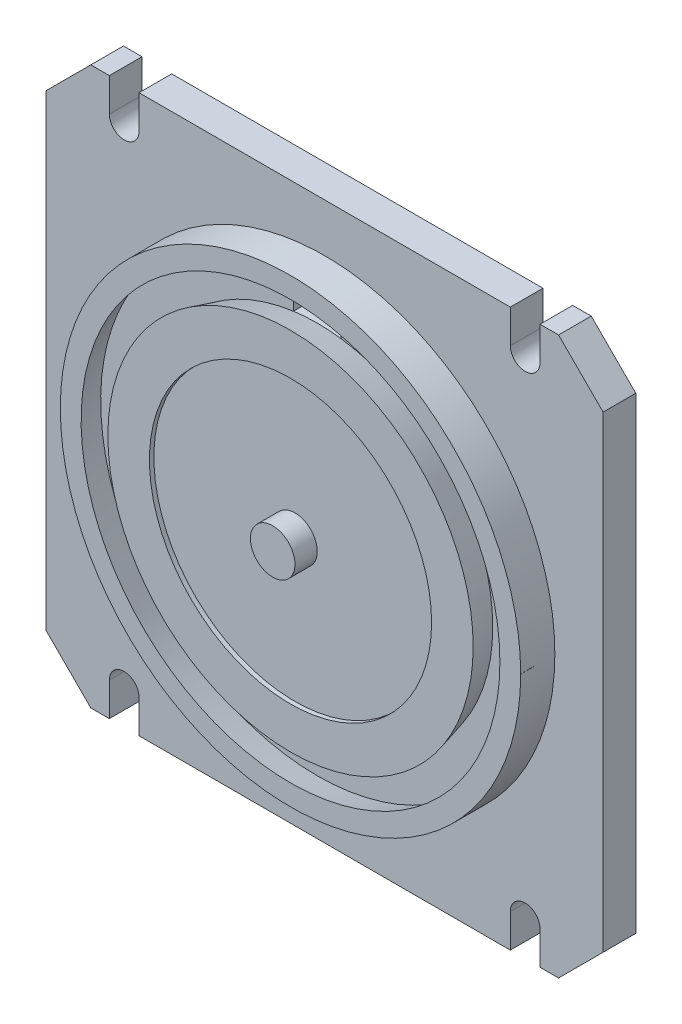
SolidWorks part; units mm, degrees
ref_plane "前视基准面" through (0, 0, 0) normal (0, 0, 1) x (1, 0, 0)
ref_plane "上视基准面" through (0, 0, 0) normal (0, 1, 0) x (1, 0, 0)
ref_plane "右视基准面" through (0, 0, 0) normal (1, 0, 0) x (0, 0, -1)
sketch "草图1" plane through (0, 0, 0) normal (0, 0, 1) x (1, 0, 0)
  line L1 (-187.5, -187.5) -> (187.5, -187.5)
  line L2 (-187.5, -187.5) -> (-187.5, 187.5)
  line L3 (-187.5, 187.5) -> (187.5, 187.5)
  line L4 (187.5, -187.5) -> (187.5, 187.5)
  line L5 (-187.5, -187.5) -> (187.5, 187.5) construction
  line L6 (-187.5, 187.5) -> (187.5, -187.5) construction
  point P0 (0, 0)
  dimension "D1" = 375
extrude "凸台-拉伸1" add sketch "草图1" along normal blind 22
chamfer "倒角1" distance 30 angle 45 4 edges at (187.5, -187.5, 11) (-187.5, -187.5, 11) (-187.5, 187.5, 11) (187.5, 187.5, 11)
sketch "草图2" plane through (0, 0, 22) normal (0, 0, 1) x (1, 0, 0)
  line L0 (135, -187.5) -> (135, -165) construction
  line L1 (-157.5, -187.5) -> (157.5, -187.5) construction
  line L2 (125, -187.5) -> (125, -165)
  line L3 (145, -187.5) -> (145, -165)
  line L4 (0, -12.1) -> (0, 12.1) construction
  line L5 (12.1, 0) -> (-12.1, 0) construction
  arc A0 (125, -187.5) -> (145, -187.5) centre (135, -187.5) ccw
  arc A1 (145, -165) -> (125, -165) centre (135, -165) ccw
  point P4 (135, -176.25)
  dimension "D1" = 20
  dimension "D2" = 135
  dimension "D3" = 165
extrude "切除-拉伸1" cut sketch "草图2" against normal through all
mirror "镜向1" about plane through (0, 0, 0) normal (0, 1, 0) of "切除-拉伸1" second plane through (0, 0, 0) second plane normal (1, 0, 0)
sketch "草图3" plane through (0, 0, 22) normal (0, 0, 1) x (1, 0, 0)
  circle A0 centre (0, 0) radius 155
  dimension "D1" = 310
extrude "凸台-拉伸2" add sketch "草图3" along normal blind 23
sketch "草图4" plane through (0, 0, 45) normal (0, 0, 1) x (1, 0, 0)
  circle A0 centre (0, 0) radius 95
  dimension "D1" = 190
extrude "切除-拉伸2" cut sketch "草图4" against normal blind 3
sketch "草图5" plane through (0, 0, 42) normal (0, 0, 1) x (1, 0, 0)
  circle A0 centre (0, 0) radius 15
  dimension "D1" = 30
extrude "凸台-拉伸3" add sketch "草图5" along normal blind 15
sketch "草图6" plane through (0, 0, 0) normal (1, 0, 0) x (0, 0, -1)
  line L0 (-100.6659, -132) -> (56.0634, -132) construction
  line L1 (31.35, 0) -> (-31.35, 0) construction
  line L2 (0, 0) -> (137.7485, 0) construction
  line L3 (0, -157.5) -> (0, 157.5) construction
  line L4 (-78.5885, -132) -> (-27, -118.1769)
  line L5 (-27, -118.1769) -> (-27, -145.8231)
  line L6 (-27, -145.8231) -> (-78.5885, -132)
  line L7 (-45, 155) -> (-45, -155) construction
  point P13 (-45, -141)
  point P14 (-45, -123)
  dimension "D1" = 132
  dimension "D2" = 30
  dimension "D3" = 18
  dimension "D4" = 18
revolve "切除-旋转1" cut sketch "草图6" angle 360 about L2
sketch "草图7" plane through (0, 0, 27) normal (0, 0, 1) x (1, 0, 0)
  line L0 (-16, 117.0888) -> (-16, 144.9427)
  line L1 (0, 108.8139) -> (0, 216.5114) construction
  line L2 (0, -131.1279) -> (0, 131.1279) construction
  line L3 (16, 117.0888) -> (16, 144.9427)
  circle A0 centre (0, 0) radius 118.1769 construction
  circle A1 centre (0, 0) radius 145.8231 construction
  arc A2 (16, 117.0888) -> (-16, 117.0888) centre (0, 0) ccw
  arc A3 (16, 144.9427) -> (-16, 144.9427) centre (0, 0) ccw
  arc A4 (-16, 144.9427) -> (16, 144.9427) centre (0, 0) ccw construction
  arc A5 (-16, 117.0888) -> (16, 117.0888) centre (0, 0) ccw construction
  dimension "D1" = 32
extrude "切除-拉伸3" cut sketch "草图7" against normal through all
sketch "草图8" plane through (0, 0, 0) normal (1, 0, 0) x (0, 0, -1)
  line L0 (31.35, 0) -> (-31.35, 0) construction
  line L1 (-36, 0.05) -> (-45, 0.05)
  line L2 (-36, 0.05) -> (-36, -0.05)
  line L3 (-36, -0.05) -> (-45, -0.05)
  line L4 (-45, 0.05) -> (-45, -0.05)
  line L5 (-36, 0.05) -> (-45, -0.05) construction
  line L6 (-36, -0.05) -> (-45, 0.05) construction
  line L7 (-45, 155) -> (-45, -155) construction
  point P0 (-40.5, 0)
  dimension "D1" = 9
  dimension "D2" = 0.1
wrap "包覆1" sketch "草图8" wrap type deboss source sketch "草图8" thickness 0.2 face at (155, 0, 45) parameters "D1"=0.2
mirror "镜向2" about plane through (0, 0, 0) normal (1, 0, 0) of "包覆1"
